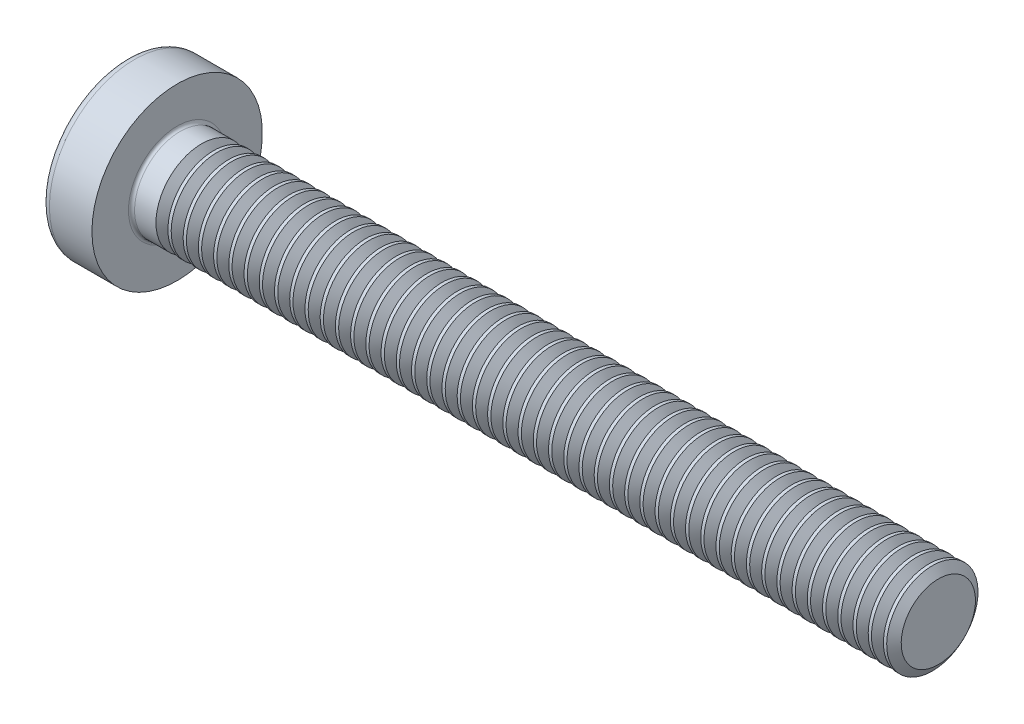
SolidWorks part; units mm, degrees
ref_plane "Plane1" through (0, 0, 0) normal (0, 0, 1) x (1, 0, 0)
ref_plane "Plane2" through (0, 0, 0) normal (0, 1, 0) x (1, 0, 0)
ref_plane "Plane3" through (0, 0, 0) normal (1, 0, 0) x (0, 0, -1)
sketch "BodySke" plane through (0, 0, 0) normal (0, 0, 1) x (1, 0, 0)
  line L0 (2.4, 1.5) -> (2.4, 2.8)
  line L1 (2.65, 6.35) -> (2.65, -3.175) construction
  line L2 (-25.4, 0) -> (127, 0) construction
  line L3 (27.4, 0) -> (0, 0)
  line L4 (2.4, 1.5) -> (27.4, 1.5)
  line L5 (27.4, 1.5) -> (27.4, 0)
  line L6 (1.0035, 2.8) -> (2.4, 2.8)
  line L8 (2.4, 6.35) -> (2.4, -3.175) construction
  arc A0 (0.7754, 2.6744) -> (0, 0) centre (5, 0) ccw
  arc A2 (0.7754, 2.6744) -> (1.0035, 2.8) centre (1.0035, 2.53) cw
  dimension "Head_fillet_rad" = 0.27
  dimension "Head_crown_rad" = 5
  dimension "Head_ht" = 2.4
  dimension "Diameter" = 3
  dimension "Length" = 25
  dimension "Head_dia" = 5.6
  dimension "Advance" = 0.5
  dimension "Thread_nom" = 25
revolve "Base-Revolve" add sketch "BodySke"
cosmetic thread "ThreadCosmetic" [suppressed]
fillet "Fillet1" radius 0.1 1 edges at (2.4, 0, 1.5)
sketch "Sketch3" plane through (0, 0, 0) normal (1, 0, 0) x (0, 0, -1)
  line L0 (0.37, -1.4) -> (-0.37, -1.4)
  line L1 (0.37, -1.4) -> (0.37, 1.4)
  line L2 (-0.37, 1.4) -> (0.37, 1.4)
  line L3 (-0.37, 1.4) -> (-0.37, -1.4)
  dimension "D1" = 1.4
  dimension "Cross_dia" = 2.8
  dimension "D2" = 0.37
  dimension "Cross_width" = 0.74
ref_plane "Plane4" through (1.75, 0, 0) normal (1, 0, 0) x (0, 0, -1)
sketch "Sketch4" plane through (1.75, 0, 0) normal (1, 0, 0) x (0, 0, -1)
  line L0 (0.37, -0.5275) -> (-0.37, -0.5275)
  line L1 (0.37, -0.5275) -> (0.37, 0.5275)
  line L2 (-0.37, 0.5275) -> (0.37, 0.5275)
  line L3 (-0.37, 0.5275) -> (-0.37, -0.5275)
  dimension "D1" = 0.74
  dimension "D2" = 1.055
  dimension "D3" = 0.37
  dimension "D4" = 0.5275
loft "Recess" cut profiles "Sketch3", "Sketch4"
pattern_circular "RecPat" count 2 every 90 about axis through (0, 0, 0) along (1, 0, 0) of "Recess"
sketch "RecCorSke" plane through (0, 0, 0) normal (0, 0, 1) x (1, 0, 0)
  line L0 (-3.175, 0) -> (15.875, 0) construction
  line L1 (-25.4, 0) -> (127, 0) construction
  line L2 (0, 0) -> (0, 0.6784)
  line L3 (0, 0.6784) -> (1.75, 0.556)
  line L4 (1.75, 0.556) -> (1.9307, 0)
  line L5 (1.9307, 0) -> (0, 0)
  dimension "Diameter" = 1.112
  dimension "Depth" = 1.75
  dimension "Draft_angle" = 4
  dimension "Bottom_angle" = 18
revolve "RecessCore" cut sketch "RecCorSke" angle 360 about L0
sketch "ThdSchSke" plane through (0, 0, 0) normal (0, 0, 1) x (1, 0, 0)
  line L0 (3.4, -1.2195) -> (3.2036, -1.5)
  line L1 (3.4, -1.2195) -> (3.5964, -1.5)
  line L2 (3.5964, -1.5) -> (3.5964, -1.875)
  line L3 (-3.175, 0) -> (5.1513, 0) construction
  line L5 (3.5964, -1.875) -> (3.2036, -1.875)
  line L6 (3.2036, -1.875) -> (3.2036, -1.5)
  dimension "Thread_minor" = 2.439
  dimension "Diameter" = 3
  dimension "Start" = 3.4
  dimension "SideAngle" = 55
  dimension "VeeAngle" = 70
  dimension "Overcut" = 3.75
revolve "ThreadSchematic" cut sketch "ThdSchSke" angle 360 about L3
pattern_linear "ThdSchPat" count 49 spacing 0.5 along (1, 0, 0) of "ThreadSchematic"
equation "\"D1@Sketch3\" = \"Cross_dia@Sketch3\" / 2"
equation "\"D2@Sketch3\" = \"Cross_width@Sketch3\" / 2"
equation "\"Depth@RecCorSke\" = \"Cross_depth@Plane4\""
equation "\"D1@Sketch4\" = \"Cross_width@Sketch3\""
equation "\"D2@Sketch4\" = \"Cross_dia@Sketch3\" - 2.0 * \"Cross_depth@Plane4\" * tan(26.5  * 0.017453292)"
equation "\"D3@Sketch4\" = \"D1@Sketch4\" / 2"
equation "\"D4@Sketch4\" = \"D2@Sketch4\" / 2"
equation "\"Thread_length@ThreadCosmetic\" = ((sgn( (\"Length@BodySke\" - \"Advance@BodySke\" * 2.0 ) - \"Thread_nom@BodySke\" )-1)*( (\"Length@BodySke\" - \"Advance@BodySke\" * 2.0 ) - \"Thread_nom@BodySke\" ))/-2+ \"Thread_nom@BodySke\""
equation "\"Thread_minor@ThdSchSke\" = \"Thread_minor@ThreadCosmetic\""
equation "\"Diameter@ThdSchSke\" = \"Diameter@BodySke\""
equation "\"Overcut@ThdSchSke\" = \"Diameter@BodySke\" * 1.25"
equation "\"Start@ThdSchSke\" = \"Head_ht@BodySke\" + \"Length@BodySke\" - \"Thread_length@ThreadCosmetic\"  '---Non-countersunk---"
equation "\"Num_threads@ThdSchPat\" = int( \"Thread_length@ThreadCosmetic\" / \"Advance@BodySke\" + 0.999 )  + 1"
equation "\"Advance@ThdSchPat\" = \"Thread_length@ThreadCosmetic\" /  (\"Num_threads@ThdSchPat\" - 1) 'relax it"
